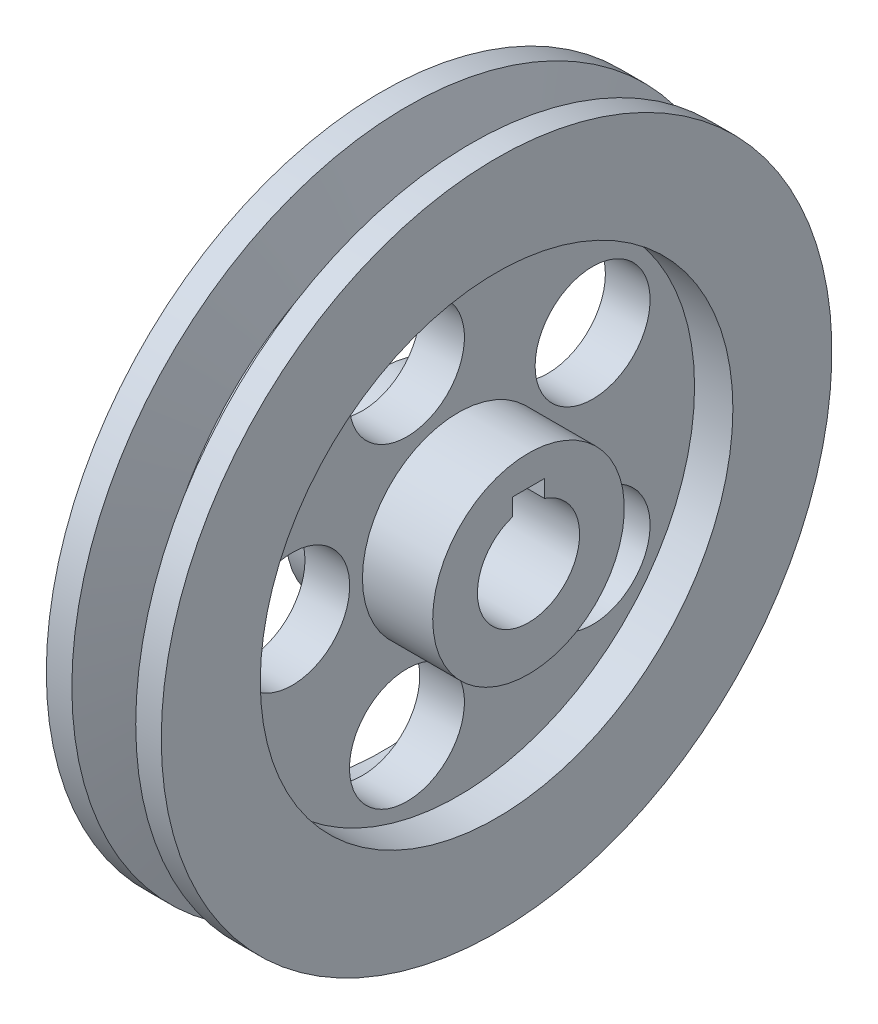
SolidWorks part; units mm, degrees
ref_plane "前视基准面" through (0, 0, 0) normal (0, 0, 1) x (1, 0, 0)
ref_plane "上视基准面" through (0, 0, 0) normal (0, 1, 0) x (1, 0, 0)
ref_plane "右视基准面" through (0, 0, 0) normal (1, 0, 0) x (0, 0, -1)
other "Configuration Table"
sketch "草图1" plane through (0, 0, 0) normal (0, 0, 1) x (1, 0, 0)
  line L0 (-5, 0) -> (28, 0) construction
  line L1 (0, 0) -> (23, 0)
  line L2 (23, 0) -> (23, 15)
  line L3 (23, 15) -> (12, 15)
  line L4 (12, 15) -> (12, 37)
  line L5 (12, 37) -> (18, 37)
  line L6 (18, 37) -> (18, 52.5)
  line L7 (18, 52.5) -> (14, 52.5)
  line L8 (14, 52.5) -> (11.3205, 42.5)
  line L9 (11.3205, 42.5) -> (6.6795, 42.5)
  line L10 (6.6795, 42.5) -> (4, 52.5)
  line L11 (4, 52.5) -> (0, 52.5)
  line L12 (0, 52.5) -> (0, 37)
  line L13 (0, 37) -> (5, 37)
  line L14 (5, 37) -> (5, 15)
  line L15 (5, 15) -> (0, 15)
  line L16 (0, 15) -> (0, 0)
revolve "01_BODY" add sketch "草图1" angle 360 about L0
ref_plane "P_02_BORE" through (-1, 0, 0) normal (1, 0, 0) x (0, 0, -1)
sketch "草图2" plane through (-1, 0, 0) normal (1, 0, 0) x (0, 0, -1)
  circle A0 centre (0, 0) radius 8
extrude "02_BORE" cut sketch "草图2" along normal blind 25
ref_plane "P_KEY" through (-1, 0, 0) normal (1, 0, 0) x (0, 0, -1)
sketch "草图3" plane through (-1, 0, 0) normal (1, 0, 0) x (0, 0, -1)
  line L0 (-2.5, 7) -> (2.5, 7)
  line L1 (2.5, 7) -> (2.5, 10.3)
  line L2 (2.5, 10.3) -> (-2.5, 10.3)
  line L3 (-2.5, 10.3) -> (-2.5, 7)
extrude "03_KEYWAY" cut sketch "草图3" along normal blind 25
ref_plane "P_04_HOLE_0" through (4, 0, 0) normal (1, 0, 0) x (0, 0, -1)
sketch "草图4" plane through (4, 0, 0) normal (1, 0, 0) x (0, 0, -1)
  circle A0 centre (-26, 0) radius 9
extrude "04_HOLE_0" cut sketch "草图4" along normal blind 9
ref_plane "P_04_HOLE_1" through (4, 0, 0) normal (1, 0, 0) x (0, 0, -1)
sketch "草图5" plane through (4, 0, 0) normal (1, 0, 0) x (0, 0, -1)
  circle A0 centre (-8.0344, -24.7275) radius 9
extrude "04_HOLE_1" cut sketch "草图5" along normal blind 9
ref_plane "P_04_HOLE_2" through (4, 0, 0) normal (1, 0, 0) x (0, 0, -1)
sketch "草图6" plane through (4, 0, 0) normal (1, 0, 0) x (0, 0, -1)
  circle A0 centre (21.0344, -15.2824) radius 9
extrude "04_HOLE_2" cut sketch "草图6" along normal blind 9
ref_plane "P_04_HOLE_3" through (4, 0, 0) normal (1, 0, 0) x (0, 0, -1)
sketch "草图7" plane through (4, 0, 0) normal (1, 0, 0) x (0, 0, -1)
  circle A0 centre (21.0344, 15.2824) radius 9
extrude "04_HOLE_3" cut sketch "草图7" along normal blind 9
ref_plane "P_04_HOLE_4" through (4, 0, 0) normal (1, 0, 0) x (0, 0, -1)
sketch "草图8" plane through (4, 0, 0) normal (1, 0, 0) x (0, 0, -1)
  circle A0 centre (-8.0344, 24.7275) radius 9
extrude "04_HOLE_4" cut sketch "草图8" along normal blind 9
